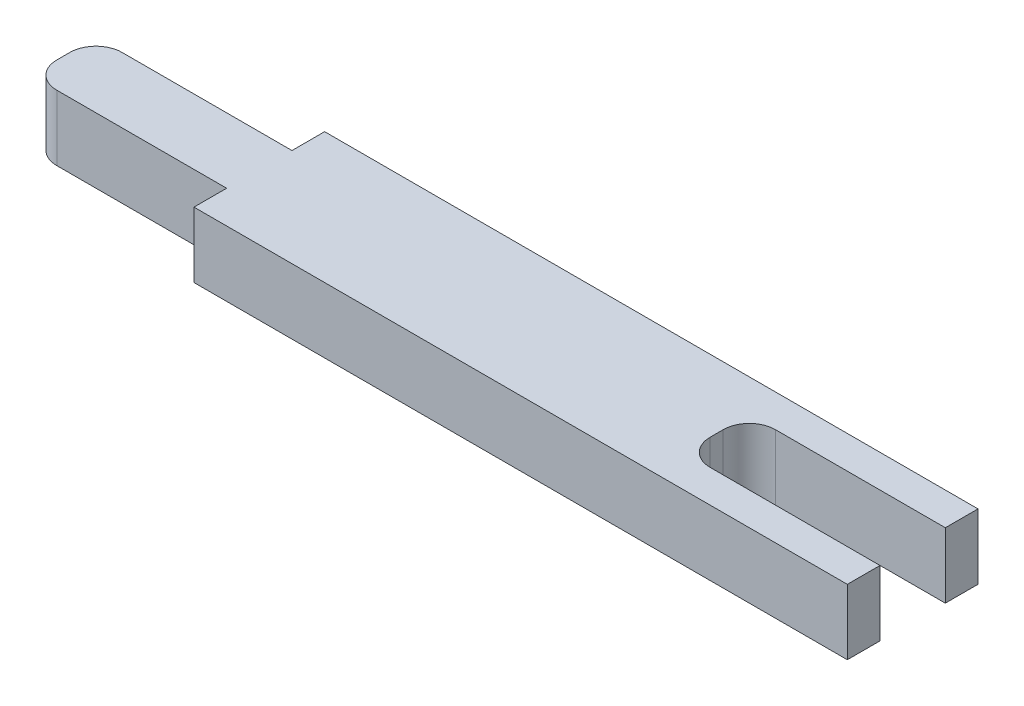
SolidWorks part; units mm, degrees
ref_plane "Alzado" through (0, 0, 0) normal (0, 0, 1) x (1, 0, 0)
ref_plane "Planta" through (0, 0, 0) normal (0, 1, 0) x (1, 0, 0)
ref_plane "Vista lateral" through (0, 0, 0) normal (1, 0, 0) x (0, 0, -1)
sketch "Croquis1" plane through (0, 0, 0) normal (0, 1, 0) x (1, 0, 0)
  line L1 (0, 0) -> (50, 0)
  line L2 (0, 0) -> (0, 10)
  line L3 (0, 10) -> (50, 10)
  line L4 (50, 0) -> (50, 10)
  dimension "D1" = 10
  dimension "D2" = 50
extrude "Saliente-Extruir1" add sketch "Croquis1" along normal mid plane 5
sketch "Croquis2" plane through (0, 2.5, 0) normal (0, 1, 0) x (1, 0, 0)
  line L0 (50, 0) -> (50, 10) construction
  line L1 (50, 7.5) -> (37, 7.5)
  line L2 (50, 7.5) -> (50, 2.5)
  line L3 (50, 2.5) -> (37, 2.5)
  line L4 (35, 5.5) -> (35, 4.5)
  line L5 (0, 5) -> (88.2165, 5) construction
  line L6 (0, 10) -> (0, 0) construction
  arc A0 (37, 2.5) -> (35, 4.5) centre (37, 4.5) cw
  arc A1 (37, 7.5) -> (35, 5.5) centre (37, 5.5) ccw
  point P10 (35, 5)
  point P15 (35, 7.5)
  dimension "D3" = 2
  dimension "D1" = 5
  dimension "D2" = 15
extrude "Cortar-Extruir1" cut sketch "Croquis2" against normal through all
sketch "Croquis3" plane through (0, 2.5, 0) normal (0, 1, 0) x (1, 0, 0)
  line L0 (0, 10) -> (0, 0) construction
  line L1 (0, 2.5) -> (-13, 2.5)
  line L2 (0, 2.5) -> (0, 7.5)
  line L3 (0, 7.5) -> (-13, 7.5)
  line L4 (-15, 4.5) -> (-15, 5.5)
  arc A0 (-13, 2.5) -> (-15, 4.5) centre (-13, 4.5) cw
  arc A1 (-13, 7.5) -> (-15, 5.5) centre (-13, 5.5) ccw
  point P6 (0, 5)
  point P7 (0, 5)
  point P10 (-15, 2.5)
  point P13 (-15, 7.5)
  dimension "D3" = 2
  dimension "D1" = 15
  dimension "D2" = 5
extrude "Saliente-Extruir2" add sketch "Croquis3" against normal blind 5
